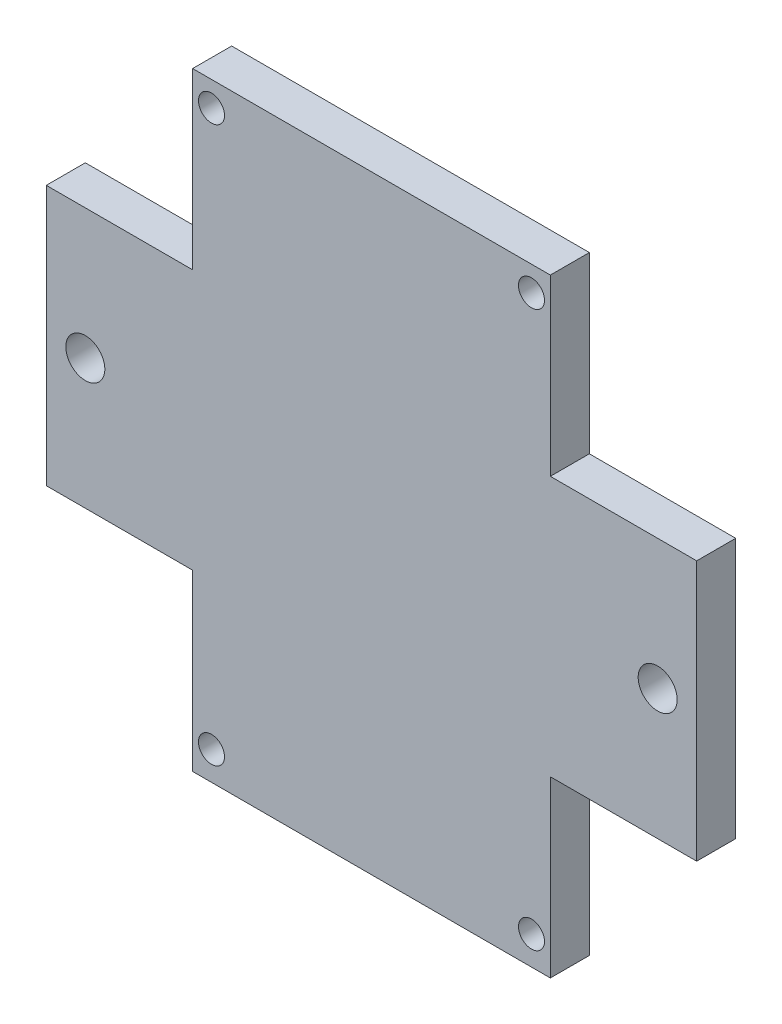
SolidWorks part; units mm, degrees
ref_plane "Front Plane" through (0, 0, 0) normal (0, 0, 1) x (1, 0, 0)
ref_plane "Top Plane" through (0, 0, 0) normal (0, 1, 0) x (1, 0, 0)
ref_plane "Right Plane" through (0, 0, 0) normal (1, 0, 0) x (0, 0, -1)
sketch "草图2" plane through (0, 0, 0) normal (0, 1, 0) x (1, 0, 0)
  line L1 (-13.75, 1.5) -> (13.75, 1.5)
  line L2 (-13.75, 1.5) -> (-13.75, -1.5)
  line L3 (-13.75, -1.5) -> (13.75, -1.5)
  line L4 (13.75, 1.5) -> (13.75, -1.5)
  line L5 (-13.75, 1.5) -> (13.75, -1.5) construction
  line L6 (-13.75, -1.5) -> (13.75, 1.5) construction
  point P0 (0, 0)
  dimension "D1" = 27.5
  dimension "D2" = 3
extrude "凸台-拉伸1" add sketch "草图2" along normal blind 46.8
sketch "草图3" plane through (0, 0, -1.5) normal (0, 0, -1) x (-1, 0, 0)
  line L0 (0, 0) -> (0, 46.8) construction
  line L1 (-13.75, 0) -> (13.75, 0) construction
  line L2 (-13.75, 46.8) -> (13.75, 46.8) construction
  circle A0 centre (-12.3, 44.8931) radius 1
  circle A1 centre (-12.3, 2.2) radius 1
  circle A2 centre (12.3, 2.2) radius 1
  circle A3 centre (12.3, 44.8931) radius 1
  dimension "D1" = 2
  dimension "D2" = 2.2
  dimension "D3" = 12.3
extrude "切除-拉伸1" cut sketch "草图3" against normal blind 46.8
sketch "草图4" plane through (0, 0, 0) normal (1, 0, 0) x (0, 0, -1)
  line L0 (-1.5, 46.8) -> (-1.5, 0) construction
  line L1 (-1.5, 33.4) -> (1.5, 33.4)
  line L2 (-1.5, 33.4) -> (-1.5, 13.4)
  line L3 (-1.5, 13.4) -> (1.5, 13.4)
  line L4 (1.5, 33.4) -> (1.5, 13.4)
  line L5 (1.5, 46.8) -> (1.5, 0) construction
  line L6 (-1.5, 13.4) -> (1.5, 33.4) construction
  line L7 (1.5, 0) -> (-1.5, 46.8) construction
  point P8 (0, 23.4)
  point P13 (0, 23.4)
  dimension "D1" = 20
extrude "凸台-拉伸2" add sketch "草图4" along normal blind 25 and the other way blind 25
sketch "草图5" plane through (0, 0, -1.5) normal (0, 0, -1) x (-1, 0, 0)
  line L0 (-25, 23.4) -> (25, 23.4) construction
  line L1 (-25, 13.4) -> (-25, 33.4) construction
  line L2 (25, 13.4) -> (25, 33.4) construction
  line L3 (0, 0) -> (0, 36.3141) construction
  circle A0 centre (-22, 23.4) radius 1.5
  circle A1 centre (22, 23.4) radius 1.5
  dimension "D1" = 3
  dimension "D2" = 22
  dimension "D3" = 22
extrude "切除-拉伸2" cut sketch "草图5" against normal blind 25
